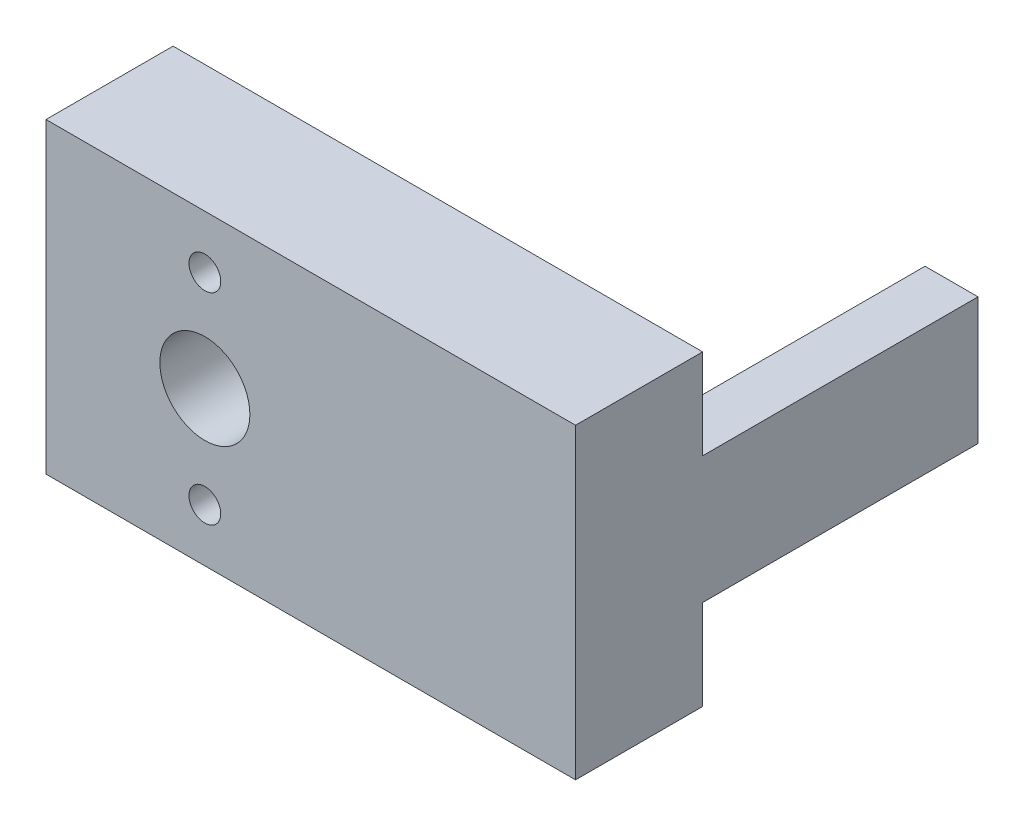
SolidWorks part; units mm, degrees
ref_plane "Front Plane" through (0, 0, 0) normal (0, 0, 1) x (1, 0, 0)
ref_plane "Top Plane" through (0, 0, 0) normal (0, 1, 0) x (1, 0, 0)
ref_plane "Right Plane" through (0, 0, 0) normal (1, 0, 0) x (0, 0, -1)
sketch "Sketch1" plane through (0, 0, 0) normal (0, 0, 1) x (1, 0, 0)
  line L1 (-27.5, 14.5) -> (22.5, 14.5)
  line L2 (-27.5, 14.5) -> (-27.5, -14.5)
  line L3 (-27.5, -14.5) -> (22.5, -14.5)
  line L4 (22.5, 14.5) -> (22.5, -14.5)
  point P0 (0, 0)
  point P5 (0, 0)
  dimension "D1" = 50
  dimension "D2" = 29
  dimension "D3" = 14.5
  dimension "D4" = 22.5
extrude "Boss-Extrude1" add sketch "Sketch1" along normal blind 12
sketch "Sketch2" plane through (0, 0, 12) normal (0, 0, 1) x (1, 0, 0)
  line L0 (22.5, -14.5) -> (22.5, 14.5) construction
  line L1 (22.5, 14.5) -> (-27.5, 14.5) construction
  circle A1 centre (-12.5, 0) radius 4.25
  dimension "D1" = 8.5
  dimension "D2" = 35
  dimension "D3" = 14.5
extrude "Cut-Extrude1" cut sketch "Sketch2" against normal blind 12
sketch "Sketch6" plane through (0, 0, 12) normal (0, 0, 1) x (1, 0, 0)
  line L0 (22.5, 14.5) -> (-27.5, 14.5) construction
  line L1 (-27.5, -14.5) -> (22.5, -14.5) construction
  line L3 (-27.5, 14.5) -> (-27.5, -14.5) construction
  circle A0 centre (-12.5, 9.5) radius 1.5
  circle A1 centre (-12.5, -9.5) radius 1.5
  dimension "D1" = 5
  dimension "D3" = 3
  dimension "D4" = 3
  dimension "D2" = 5
  dimension "D5" = 15
extrude "Cut-Extrude2" cut sketch "Sketch6" against normal blind 12
sketch "Sketch3" plane through (0, 0, 0) normal (0, 0, -1) x (-1, 0, 0)
  line L6 (-22.5, 6) -> (-17.5, 6)
  line L7 (-22.5, -14.5) -> (-22.5, 14.5) construction
  line L8 (-17.5, 6) -> (-17.5, -6)
  line L9 (-17.5, -6) -> (-22.5, -6)
  line L10 (-22.5, -6) -> (-22.5, 6)
  line L13 (27.5, -14.5) -> (-22.5, -14.5) construction
  line L14 (-22.5, 14.5) -> (27.5, 14.5) construction
  dimension "D1" = 5
  dimension "D2" = 8.5
  dimension "D3" = 12
  dimension "D5" = 8.5
extrude "Boss-Extrude2" add sketch "Sketch3" along normal blind 26
